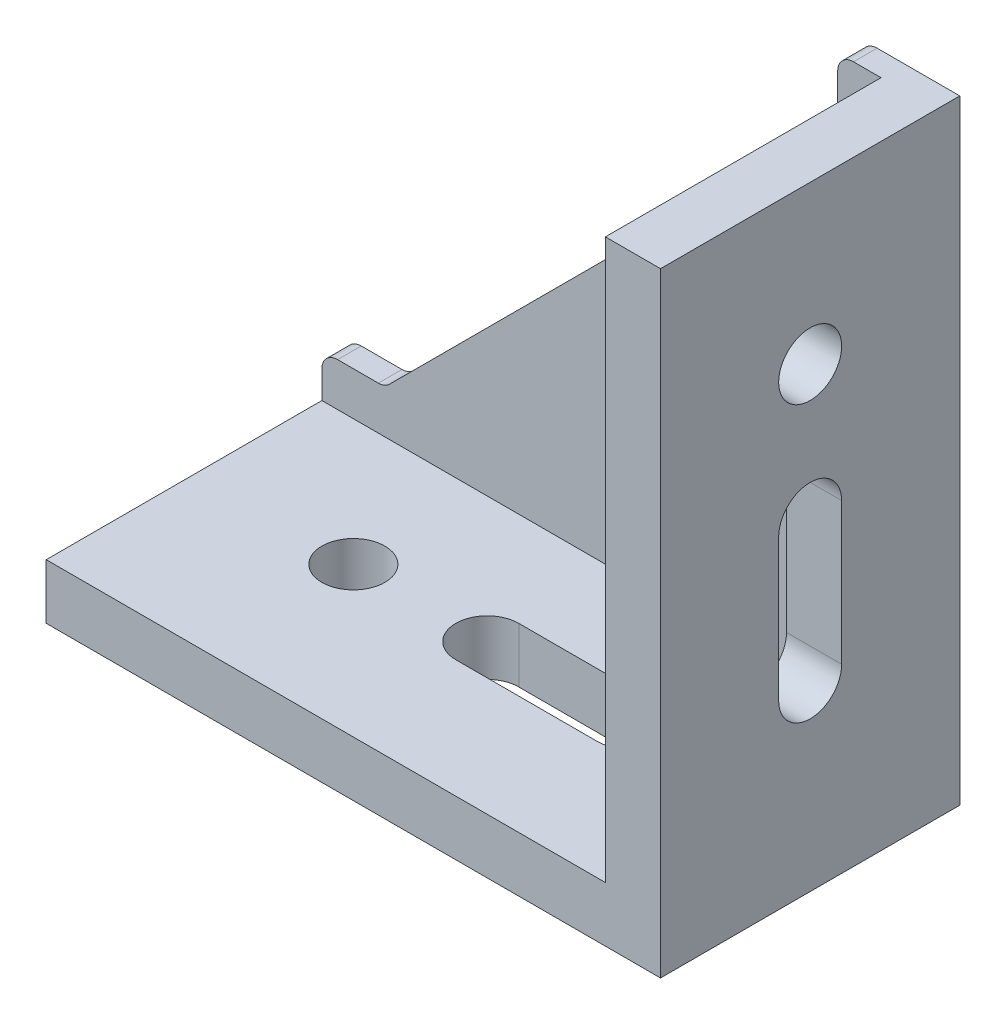
SolidWorks part; units mm, degrees
material "1060 合金"
ref_plane "前视基准面" through (0, 0, 0) normal (0, 0, 1) x (1, 0, 0)
ref_plane "上视基准面" through (0, 0, 0) normal (0, 1, 0) x (1, 0, 0)
ref_plane "右视基准面" through (0, 0, 0) normal (1, 0, 0) x (0, 0, -1)
sketch "草图1" plane through (0, 0, 0) normal (0, 0, 1) x (1, 0, 0)
  line L0 (0, 0) -> (78, 0)
  line L1 (78, 0) -> (78, 78)
  line L2 (0, 0) -> (0, 7)
  line L3 (0, 7) -> (71, 7)
  line L4 (71, 7) -> (71, 78)
  line L5 (71, 78) -> (78, 78)
  dimension "D1" = 78
  dimension "D2" = 78
  dimension "D3" = 7
  dimension "D4" = 7
extrude "凸台-拉伸1" add sketch "草图1" along normal blind 35
sketch "草图2" plane through (0, 0, 0) normal (0, 0, -1) x (-1, 0, 0)
  line L0 (-78, 78) -> (-78, 0)
  line L1 (-78, 0) -> (0, 0)
  line L2 (-78, 78) -> (-65.5, 78)
  line L3 (-65.5, 78) -> (-65.5, 70)
  line L4 (-65.5, 70) -> (-8, 12.5)
  line L5 (-8, 12.5) -> (0, 12.5)
  line L6 (0, 12.5) -> (0, 0)
  dimension "D1" = 12.5
  dimension "D2" = 12.5
  dimension "D3" = 8
  dimension "D4" = 8
extrude "凸台-拉伸2" add sketch "草图2" along normal blind 3
sketch "草图3" plane through (71, 0, 0) normal (-1, 0, 0) x (0, 0, 1)
  line L0 (16, 68.4404) -> (16, -21.2031) construction
  line L1 (35, 78) -> (35, 7) construction
  line L2 (12, 41) -> (12, 23)
  line L3 (20, 41) -> (20, 23)
  line L4 (35, 0) -> (-3, 0) construction
  arc A0 (12, 23) -> (20, 23) centre (16, 23) ccw
  arc A1 (20, 41) -> (12, 41) centre (16, 41) ccw
  circle A2 centre (16, 58) radius 4
  dimension "D3" = 8
  dimension "D1" = 19
  dimension "D2" = 23
  dimension "D4" = 18
  dimension "D5" = 17
extrude "切除-拉伸1" cut sketch "草图3" against normal through all
sketch "草图4" plane through (0, 7, 0) normal (0, 1, 0) x (1, 0, 0)
  line L0 (-10.178, -16) -> (71.6896, -16) construction
  line L1 (0, 3) -> (8, 3) construction
  line L2 (37, -20) -> (55, -20)
  line L3 (37, -12) -> (55, -12)
  line L4 (78, -35) -> (78, 3) construction
  arc A0 (55, -20) -> (55, -12) centre (55, -16) ccw
  arc A1 (37, -12) -> (37, -20) centre (37, -16) ccw
  circle A2 centre (20, -16) radius 4
  dimension "D4" = 8
  dimension "D1" = 19
  dimension "D2" = 23
  dimension "D3" = 18
  dimension "D5" = 17
extrude "切除-拉伸2" cut sketch "草图4" against normal through all
fillet "圆角1" radius 2 2 edges at (0, 12.5, -1.5) (65.5, 78, -1.5)
fillet "圆角2" radius 2 2 edges at (8, 12.5, -1.5) (65.5, 70, -1.5)
